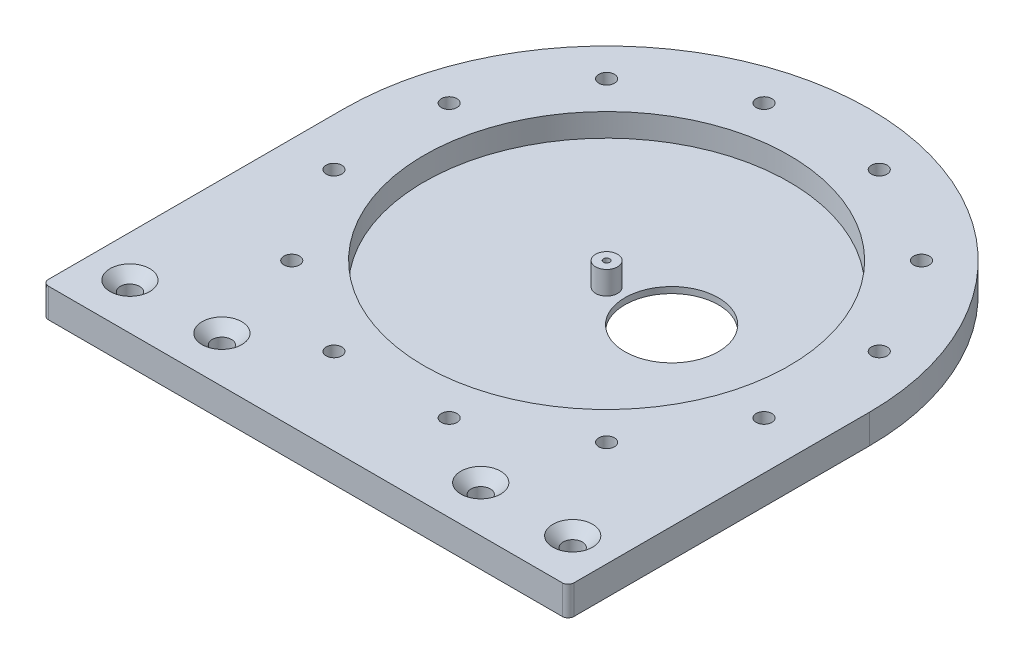
SolidWorks part; units mm, degrees
material "6061 Alloy"
ref_plane "Front Plane" through (0, 0, 0) normal (0, 0, 1) x (1, 0, 0)
ref_plane "Top Plane" through (0, 0, 0) normal (0, 1, 0) x (1, 0, 0)
ref_plane "Right Plane" through (0, 0, 0) normal (1, 0, 0) x (0, 0, -1)
sketch "Sketch1" plane through (0, 0, 0) normal (0, 1, 0) x (1, 0, 0)
  line L0 (-114.3, 0) -> (-114.3, -131.0405)
  line L1 (-114.3, -131.0405) -> (114.3, -131.0405)
  line L2 (114.3, -131.0405) -> (114.3, 0)
  line L3 (-56.1266, 56.1266) -> (-68.4745, 68.4745) construction
  line L4 (0, 0) -> (-56.1266, 56.1266) construction
  line L5 (0, 0) -> (114.3, 0) construction
  line L6 (-93.5378, -25.0634) -> (0, 0) construction
  line L7 (0, 0) -> (0, -111.0405) construction
  line L8 (114.3, -111.0405) -> (96.3, -111.0405) construction
  line L9 (96.3, -111.0405) -> (56.3, -111.0405) construction
  line L10 (56.3, -111.0405) -> (0, -111.0405) construction
  line L11 (0, -111.0405) -> (-56.3, -111.0405) construction
  line L12 (-56.3, -111.0405) -> (-96.3, -111.0405) construction
  line L13 (-96.3, -111.0405) -> (-114.3, -111.0405) construction
  line L14 (0, -111.0405) -> (0, -131.0405) construction
  line L15 (25.0634, 93.5378) -> (0, 0) construction
  line L16 (0, 0) -> (68.4745, 68.4745) construction
  line L17 (93.5378, 25.0634) -> (0, 0) construction
  line L18 (0, 0) -> (93.5378, -25.0634) construction
  line L19 (68.4745, -68.4745) -> (0, 0) construction
  line L20 (0, 0) -> (25.0634, -93.5378) construction
  line L21 (0, 0) -> (-25.0634, 93.5378) construction
  line L22 (-93.5378, 25.0634) -> (0, 0) construction
  line L24 (-68.4745, -68.4745) -> (0, 0) construction
  line L25 (0, 0) -> (-25.0634, -93.5378) construction
  line L26 (-25.0634, 93.5378) -> (25.0634, 93.5378) construction
  arc A0 (114.3, 0) -> (-114.3, 0) centre (0, 0) ccw
  circle A1 centre (0, 0) radius 79.375 construction
  circle A2 centre (-68.4745, 68.4745) radius 1.27
  circle A3 centre (25.0634, 93.5378) radius 1.27
  circle A4 centre (68.4745, 68.4745) radius 1.27
  circle A5 centre (93.5378, 25.0634) radius 1.27
  circle A6 centre (93.5378, -25.0634) radius 1.27
  circle A7 centre (68.4745, -68.4745) radius 1.27
  circle A8 centre (25.0634, -93.5378) radius 1.27
  circle A9 centre (-25.0634, -93.5378) radius 1.27
  circle A10 centre (-68.4745, -68.4745) radius 1.27
  circle A11 centre (-93.5378, -25.0634) radius 1.27
  circle A12 centre (-93.5378, 25.0634) radius 1.27
  circle A13 centre (-25.0634, 93.5378) radius 1.27
  circle A14 centre (96.3, -111.0405) radius 1.27
  circle A15 centre (56.3, -111.0405) radius 1.27
  circle A16 centre (-56.3, -111.0405) radius 1.27
  circle A17 centre (-96.3, -111.0405) radius 1.27
  circle A18 centre (0, 0) radius 96.8375 construction
  point P36 (0, 0)
  dimension "D1" = 228.6
  dimension "D3" = 158.75
  dimension "D4" = 2.54
  dimension "D2" = 2.54
  dimension "D8" = 30
  dimension "D5" = 193.675
  dimension "D6" = 111.0405
  dimension "D7" = 20
  dimension "D9" = 30
  dimension "D10" = 30
  dimension "D11" = 30
  dimension "D12" = 30
  dimension "D13" = 30
  dimension "D14" = 30
  dimension "D15" = 30
  dimension "D16" = 30
  dimension "D17" = 30
  dimension "D18" = 30
  dimension "D19" = 18
  dimension "D20" = 40
extrude "Boss-Extrude1" add sketch "Sketch1" along normal blind 12.7
cosmetic thread "Cosmetic Thread1" parameters "D2"=19.05
cosmetic thread "Cosmetic Thread2" parameters "D2"=19.05
cosmetic thread "Cosmetic Thread3" parameters "D2"=19.05
cosmetic thread "Cosmetic Thread4" parameters "D2"=19.05
cosmetic thread "Cosmetic Thread5" parameters "D2"=19.05
cosmetic thread "Cosmetic Thread6" parameters "D2"=19.05
cosmetic thread "Cosmetic Thread7" parameters "D2"=19.05
cosmetic thread "Cosmetic Thread8" parameters "D2"=19.05
cosmetic thread "Cosmetic Thread9" parameters "D2"=19.05
cosmetic thread "Cosmetic Thread10" parameters "D2"=19.05
cosmetic thread "Cosmetic Thread11" parameters "D2"=19.05
cosmetic thread "Cosmetic Thread12" parameters "D2"=19.05
sketch "Sketch2" plane through (0, 12.7, 0) normal (0, 1, 0) x (1, 0, 0)
  circle A0 centre (0, 0) radius 79.375
  circle A1 centre (0, 0) radius 4.7625
  dimension "D1" = 158.75
  dimension "D2" = 9.525
extrude "Cut-Extrude1" cut sketch "Sketch2" against normal blind 10.033
sketch "Sketch4" plane through (0, 12.7, 0) normal (0, 1, 0) x (1, 0, 0)
  circle A0 centre (0, 0) radius 0.127
  dimension "D1" = 0.254
extrude "Cut-Extrude2" cut sketch "Sketch4" against normal through all
hole_wizard "M8x1.25 Tapped Hole1" positions "Sketch12" profile "Sketch11" tap size "M8x1.25" standard "ANSI Metric" end condition through all
sketch "Sketch12" plane through (0, 12.7, 0) normal (0, 1, 0) x (1, 0, 0)
  point P0 (-93.5378, 25.0634)
  point P3 (-93.5378, -25.0634)
  point P6 (-25.0634, 93.5378)
  point P9 (-68.4745, 68.4745)
  point P12 (25.0634, 93.5378)
  point P15 (68.4745, 68.4745)
  point P18 (93.5378, 25.0634)
  point P21 (93.5378, -25.0634)
  point P24 (68.4745, -68.4745)
  point P27 (25.0634, -93.5378)
  point P30 (-25.0634, -93.5378)
  point P33 (-68.4745, -68.4745)
sketch "Sketch11" plane through (-93.5378, 12.7, -25.0634) normal (1, 0, 0) x (0, 0, 1)
  line L0 (0, 0) -> (0, 12.7)
  line L1 (0, 12.7) -> (3.4, 12.7)
  line L2 (3.4, 12.7) -> (3.4, 0)
  line L5 (3.4, 0) -> (0, 0)
  line L11 (0, -6.35) -> (0, 107.95) construction
  dimension "Thread Major Dia." = 6.8
  dimension "Thru Tap Drill Depth" = 12.7
sketch "Sketch13" plane through (0, 0, 0) normal (0, -1, 0) x (1, 0, 0)
  circle A0 centre (70.9, 132.4) radius 1.27
  circle A1 centre (30.9, 132.4) radius 1.27
  circle A2 centre (-30.9, 132.4) radius 1.27
  circle A3 centre (-70.9, 132.4) radius 1.27
  dimension "D1" = 2.54
hole_wizard "CSK for M8 Flat Head Machine Screw1" positions "Sketch15" profile "Sketch14" countersink size "M8" standard "ANSI Metric"
sketch "Sketch15" plane through (0, 12.7, 0) normal (0, 1, 0) x (1, 0, 0)
  point P0 (70.9, -132.4)
  point P3 (30.9, -132.4)
  point P6 (-30.9, -132.4)
  point P9 (-70.9, -132.4)
sketch "Sketch14" plane through (70.9, 12.7, 132.4) normal (1, 0, 0) x (0, 0, 1)
  line L0 (0, 0) -> (0, 12.7)
  line L1 (0, 12.7) -> (4.2, 12.7)
  line L2 (4.2, 12.7) -> (4.2, 4.45)
  line L3 (4.2, 4.45) -> (8.65, 0)
  line L5 (8.65, 0) -> (0, 0)
  line L6 (-4.2, 4.45) -> (-8.65, 0) construction
  line L11 (0, -6.35) -> (0, 107.95) construction
  dimension "Thru Hole Dia." = 8.4
  dimension "Thru Hole Depth" = 12.7
  dimension "Near C'Sink Dia." = 17.3
  dimension "Near C'Sink Angle" = 90
fillet "Fillet1" radius 2.54 2 edges at (-114.3, 6.35, 131.0405) (114.3, 6.35, 131.0405)
hole_wizard "CSK for M8 Flat Head Machine Screw3" positions "Sketch20" profile "Sketch19" countersink size "M8" standard "ANSI Metric" end condition through all
sketch "Sketch20" plane through (0, 12.7, 0) normal (0, 1, 0) x (1, 0, 0)
  point P0 (-96.3, -111.0405)
  point P3 (-56.3, -111.0405)
  point P6 (56.3, -111.0405)
  point P9 (96.3, -111.0405)
sketch "Sketch19" plane through (-96.3, 12.7, 111.0405) normal (1, 0, 0) x (0, 0, 1)
  line L0 (0, 0) -> (0, 12.7)
  line L1 (0, 12.7) -> (4.2, 12.7)
  line L2 (4.2, 12.7) -> (4.2, 4.45)
  line L3 (4.2, 4.45) -> (8.65, 0)
  line L5 (8.65, 0) -> (0, 0)
  line L6 (-4.2, 4.45) -> (-8.65, 0) construction
  line L11 (0, -6.35) -> (0, 107.95) construction
  dimension "Thru Hole Dia." = 8.4
  dimension "Thru Hole Depth" = 12.7
  dimension "Near C'Sink Dia." = 17.3
  dimension "Near C'Sink Angle" = 90
sketch "Sketch22" plane through (0, 2.667, 0) normal (0, 1, 0) x (1, 0, 0)
  line L0 (0, 0) -> (28.2843, 0) construction
  line L1 (4.7625, 0) -> (7.9375, 0) construction
  circle A0 centre (28.2843, 0) radius 20.3468
  circle A1 centre (0, 0) radius 4.7625 construction
  dimension "D2" = 3.175
  dimension "D1" = 28.2843
extrude "Cut-Extrude3" cut sketch "Sketch22" against normal through all
hole_wizard "#6-32 Tapped Hole2" positions "Sketch26" profile "Sketch25" tap size "#6-32" standard "ANSI Inch" end condition through all
sketch "Sketch26" plane through (0, 12.7, 0) normal (0, 1, 0) x (1, 0, 0)
  point P0 (0, 0)
cosmetic thread "Hole Thread2" parameters "D2"=3.5052
sketch "Sketch25" plane through (0, 12.7, 0) normal (1, 0, 0) x (0, 0, 1)
  line L0 (0, 0) -> (0, 12.7)
  line L1 (0, 12.7) -> (1.3525, 12.7)
  line L2 (1.3525, 12.7) -> (1.3525, 0)
  line L5 (1.3525, 0) -> (0, 0)
  line L11 (0, -6.35) -> (0, 107.95) construction
  dimension "Thru Tap Drill Dia." = 2.7051
  dimension "Thru Tap Drill Depth" = 12.7
